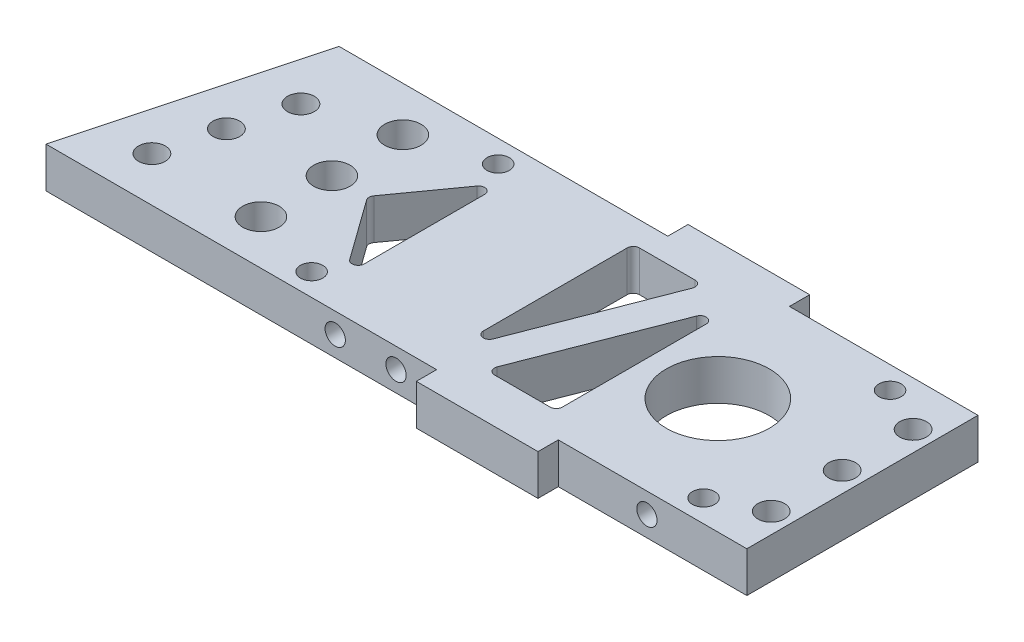
SolidWorks part; units mm, degrees
material "7075-T6, Chapa (SS)"
ref_plane "Plano frontal" through (0, 0, 0) normal (0, 0, 1) x (1, 0, 0)
ref_plane "Plano superior" through (0, 0, 0) normal (0, 1, 0) x (1, 0, 0)
ref_plane "Plano direito" through (0, 0, 0) normal (1, 0, 0) x (0, 0, -1)
sketch "Esboço1" plane through (0, 0, 0) normal (0, 0, 1) x (1, 0, 0)
  line L1 (0, 0) -> (138.453, 0)
  line L2 (0, 0) -> (0, 64)
  line L3 (0, 64) -> (240, 64)
  line L7 (250, 64) -> (250, 0)
  line L8 (240, 64) -> (250, 64)
  line L13 (250, 0) -> (138.453, 0)
  dimension "D1" = 64
  dimension "D2" = 240
  dimension "D4" = 10
sketch "Esboço2" plane through (0, 0, 0) normal (0, 1, 0) x (1, 0, 0)
  line L0 (0, 0) -> (96.32, 0)
  line L2 (0, 0) -> (0, 57)
  line L4 (172.82, 0) -> (172.82, 57)
  line L10 (126.32, 0) -> (126.32, -5)
  line L11 (126.32, -5) -> (96.32, -5)
  line L12 (96.32, 0) -> (96.32, -5)
  line L14 (126.32, 57) -> (126.32, 62)
  line L15 (126.32, 62) -> (96.32, 62)
  line L16 (96.32, 57) -> (96.32, 62)
  line L21 (0, 57) -> (96.32, 57)
  line L22 (126.32, 57) -> (172.82, 57)
  line L23 (126.32, 0) -> (172.82, 0)
  dimension "D1" = 172.82
  dimension "D2" = 57
  dimension "D3" = 30
  dimension "D4" = 46.5
  dimension "D6" = 5
  dimension "D7" = 5
  dimension "D9" = 46.5
extrude "Ressalto-extrusão1" add sketch "Esboço2" along normal blind 10
hole_wizard "Furo com folga de M61" positions "Esboço3" profile "Esboço4" hole size "M6" standard "ISO"
sketch "Esboço3" plane through (0, 10, 0) normal (0, 1, 0) x (1, 0, 0)
  line L0 (167.82, 57) -> (167.82, 46) construction
  line L1 (172.82, 57) -> (126.32, 57) construction
  line L4 (167.82, 11) -> (167.82, 0) construction
  line L5 (126.32, 0) -> (172.82, 0) construction
  line L7 (172.82, 0) -> (172.82, 57) construction
  line L8 (167.82, 46) -> (167.82, 11) construction
  point P0 (167.82, 46)
  point P2 (167.82, 28.5)
  point P4 (167.82, 11)
  dimension "D1" = 5
  dimension "D2" = 11
  dimension "D3" = 11
  dimension "D4" = 5
sketch "Esboço4" plane through (167.82, 10, -46) normal (1, 0, 0) x (0, 0, 1)
  line L0 (0, 0) -> (0, 16.9828)
  line L1 (0, 16.9828) -> (3.3, 15)
  line L2 (3.3, 15) -> (3.3, 0)
  line L5 (3.3, 0) -> (0, 0)
  line L10 (0, 16.9828) -> (-3.3, 15) construction
  line L11 (0, -6.35) -> (0, 107.95) construction
  dimension "Hole Dia." = 6.6
  dimension "Hole Depth" = 15
  dimension "Drill Angle" = 118
sketch "Esboço5" plane through (0, 10, 0) normal (0, 1, 0) x (1, 0, 0)
  line L0 (172.82, 0) -> (172.82, 57) construction
  line L1 (137.17, 57) -> (137.17, 28.5) construction
  line L2 (172.82, 57) -> (126.32, 57) construction
  line L3 (137.17, 28.5) -> (137.17, 0) construction
  line L4 (126.32, 0) -> (172.82, 0) construction
  circle A0 centre (137.17, 28.5) radius 9.525
  dimension "D1" = 19.05
  dimension "D2" = 35.65
  dimension "D3" = 28.5
extrude "Corte-extrusão1" cut sketch "Esboço5" against normal through all
sketch "Esboço6" plane through (0, 10, 0) normal (0, 1, 0) x (1, 0, 0)
  circle A0 centre (137.17, 28.5) radius 12.7
  dimension "D1" = 25.4
extrude "Corte-extrusão2" cut sketch "Esboço6" against normal through all
sketch "Esboço7" plane through (0, 10, 0) normal (0, 1, 0) x (1, 0, 0)
  line L0 (162.82, 0) -> (172.82, 17.3205)
  line L3 (126.32, 0) -> (172.82, 0) construction
  line L4 (172.82, 0) -> (172.82, 57) construction
  line L5 (183.8086, 28.5) -> (147.3586, 28.5) construction
  line L6 (162.82, 57) -> (172.82, 39.6795)
  point P7 (172.82, 28.5)
  line M11 (126.32, 0) -> (172.82, 0)
  line M12 (172.82, 0) -> (172.82, 57)
  line M13 (172.82, 57) -> (126.32, 57)
  dimension "D1" = 30
  dimension "D2" = 10
extrude "Corte-extrusão3" [suppressed] cut sketch "Esboço7" against normal through all and the other way through all contours L0 M11 M12 | L6 M13 M12
hole_wizard "Broca de rosquear para tarraxa de M61" positions "Esboço8" profile "Esboço9" hole size "M6" standard "ISO"
sketch "Esboço8" plane through (0, 0, -57) normal (0, 0, -1) x (-1, 0, 0)
  line L0 (-172.82, 5) -> (0, 5) construction
  line L1 (-172.82, 10) -> (-172.82, 0) construction
  line L2 (0, 10) -> (0, 0) construction
  line L6 (-96.32, 10) -> (-96.32, 0) construction
  line L7 (-126.32, 10) -> (-126.32, 0) construction
  point P2 (-148.17, 5)
  point P4 (-86.32, 5)
  point P42 (-71.32, 5)
  dimension "D1" = 21.85
  dimension "D2" = 15
  dimension "D3" = 10
sketch "Esboço9" plane through (148.17, 5, -57) normal (1, 0, 0) x (0, 1, 0)
  line L0 (0, 0) -> (0, 16.5022)
  line L1 (0, 16.5022) -> (2.5, 15)
  line L2 (2.5, 15) -> (2.5, 0)
  line L5 (2.5, 0) -> (0, 0)
  line L10 (0, 16.5022) -> (-2.5, 15) construction
  line L11 (0, -6.35) -> (0, 107.95) construction
  dimension "Hole Dia." = 5
  dimension "Hole Depth" = 15
  dimension "Drill Angle" = 118
hole_wizard "Broca de rosquear para tarraxa de M62" positions "Esboço14" profile "Esboço13" hole size "M6" standard "ISO"
sketch "Esboço14" plane through (0, 0, 0) normal (0, 0, 1) x (1, 0, 0)
  line L0 (0, 5) -> (172.82, 5) construction
  line L1 (0, 10) -> (0, 0) construction
  line L2 (172.82, 10) -> (172.82, 0) construction
  line L4 (96.32, 10) -> (96.32, 0) construction
  line L5 (126.32, 10) -> (126.32, 0) construction
  point P2 (86.32, 5)
  point P4 (148.17, 5)
  point P35 (71.32, 5)
  dimension "D1" = 21.85
  dimension "D2" = 10
  dimension "D3" = 15
sketch "Esboço13" plane through (86.32, 5, 0) normal (1, 0, 0) x (0, -1, 0)
  line L0 (0, 0) -> (0, 16.5022)
  line L1 (0, 16.5022) -> (2.5, 15)
  line L2 (2.5, 15) -> (2.5, 0)
  line L5 (2.5, 0) -> (0, 0)
  line L10 (0, 16.5022) -> (-2.5, 15) construction
  line L11 (0, -6.35) -> (0, 107.95) construction
  dimension "Hole Dia." = 5
  dimension "Hole Depth" = 15
  dimension "Drill Angle" = 118
hole_wizard "Furo com folga de M81" positions "Esboço15" profile "Esboço16" hole size "M8" standard "Ansi Metric" end condition through all
sketch "Esboço15" plane through (0, 10, 0) normal (0, 1, 0) x (1, 0, 0)
  line L0 (42, 57) -> (42, 0) construction
  line L1 (96.32, 57) -> (0, 57) construction
  line L2 (0, 0) -> (96.32, 0) construction
  line L4 (0, 57) -> (0, 0) construction
  point P0 (42, 46)
  point P2 (42, 28.5)
  point P4 (42, 11)
  dimension "D1" = 42
  dimension "D2" = 11
  dimension "D3" = 11
sketch "Esboço16" plane through (42, 10, -46) normal (1, 0, 0) x (0, 0, 1)
  line L0 (0, 0) -> (0, 10)
  line L1 (0, 10) -> (4.5, 10)
  line L2 (4.5, 10) -> (4.5, 0)
  line L5 (4.5, 0) -> (0, 0)
  line L11 (0, -6.35) -> (0, 107.95) construction
  dimension "Thru Hole Dia." = 9
  dimension "Thru Hole Depth" = 10
hole_wizard "Furo com folga de M51" positions "Esboço19" profile "Esboço20" hole size "M5" standard "ISO"
sketch "Esboço19" plane through (0, 10, 0) normal (0, 1, 0) x (1, 0, 0)
  line L0 (172.82, 57) -> (126.32, 57) construction
  line L1 (126.32, 0) -> (172.82, 0) construction
  line L2 (172.82, 0) -> (172.82, 57) construction
  line L3 (0, 0) -> (96.32, 0) construction
  line L4 (96.32, 57) -> (0, 57) construction
  point P0 (156.64, 51.5)
  point P2 (156.64, 5.5)
  point P4 (60, 5.5)
  point P6 (60, 51.5)
  dimension "D1" = 5.5
  dimension "D2" = 5.5
  dimension "D3" = 16.18
  dimension "D4" = 16.18
  dimension "D5" = 96.64
  dimension "D6" = 96.64
  dimension "D7" = 5.5
  dimension "D8" = 5.5
sketch "Esboço20" plane through (156.64, 10, -51.5) normal (1, 0, 0) x (0, 0, 1)
  line L0 (0, 0) -> (0, 16.6524)
  line L1 (0, 16.6524) -> (2.75, 15)
  line L2 (2.75, 15) -> (2.75, 0)
  line L5 (2.75, 0) -> (0, 0)
  line L10 (0, 16.6524) -> (-2.75, 15) construction
  line L11 (0, -6.35) -> (0, 107.95) construction
  dimension "Hole Dia." = 5.5
  dimension "Hole Depth" = 15
  dimension "Drill Angle" = 118
sketch "Esboço22" plane through (0, 10, 0) normal (0, 1, 0) x (1, 0, 0)
  line L1 (96.32, 57) -> (0, 57) construction
  line L3 (0, 0) -> (0, 57)
  line L5 (0, 0) -> (15.2731, 57)
  line L6 (0, 57) -> (15.2731, 57)
  dimension "D1" = 15
extrude "Corte-extrusão5" cut sketch "Esboço22" against normal through all
hole_wizard "Furo com folga de M62" positions "Esboço23" profile "Esboço24" hole size "M6" standard "ISO" end condition through all
sketch "Esboço23" plane through (0, 0, 0) normal (0, -1, 0) x (-1, 0, 0)
  line L0 (-27.4065, 57) -> (-12.1334, 0) construction
  line L1 (-96.32, 57) -> (-15.2731, 57) construction
  line L2 (0, 0) -> (-96.32, 0) construction
  line L4 (0, 0) -> (-15.2731, 57) construction
  point P0 (-22.8514, 40)
  point P4 (-15.0868, 11.0222)
  point P18 (-18.9691, 25.5111)
  dimension "D1" = 15
  dimension "D2" = 15
  dimension "D3" = 11.72
  dimension "D4" = 17
sketch "Esboço24" plane through (22.8514, 0, -40) normal (1, 0, 0) x (0, 0, -1)
  line L0 (0, 0) -> (0, 10)
  line L1 (0, 10) -> (3.3, 10)
  line L2 (3.3, 10) -> (3.3, 0)
  line L5 (3.3, 0) -> (0, 0)
  line L11 (0, -6.35) -> (0, 107.95) construction
  dimension "Thru Hole Dia." = 6.6
  dimension "Thru Hole Depth" = 10
sketch "Esboço25" plane through (0, 10, 0) normal (0, 1, 0) x (1, 0, 0)
  line L2 (64.82, 9) -> (50.82, 28.5)
  line L3 (50.82, 28.5) -> (64.82, 48)
  line L5 (64.82, 48) -> (64.82, 9)
  line L6 (93.82, 51) -> (111.2414, 51)
  line L7 (111.2414, 51) -> (93.82, 6)
  line L8 (93.82, 6) -> (93.82, 51)
  line L9 (102.3986, 6) -> (119.82, 51)
  line L10 (119.82, 51) -> (119.82, 6)
  line L11 (119.82, 6) -> (102.3986, 6)
  line L12 (0, 0) -> (96.32, 0) construction
  line L13 (96.32, 57) -> (15.2731, 57) construction
  line L14 (172.82, 0) -> (172.82, 57) construction
  line L16 (64.82, 28.5) -> (50.82, 28.5) construction
  dimension "D1" = 8
  dimension "D2" = 6
  dimension "D3" = 6
  dimension "D4" = 79
  dimension "D5" = 53
  dimension "D6" = 29
  dimension "D7" = 14
  dimension "D8" = 39
  dimension "D9" = 9
extrude "Corte-extrusão6" cut sketch "Esboço25" against normal through all
fillet "Filete3" radius 1.5 9 edges at (119.82, 5, -6) (102.3986, 5, -6) (111.2414, 5, -51) (119.82, 5, -51) (93.82, 5, -6) (93.82, 5, -51) (64.82, 5, -48) (64.82, 5, -9) (50.82, 5, -28.5)
